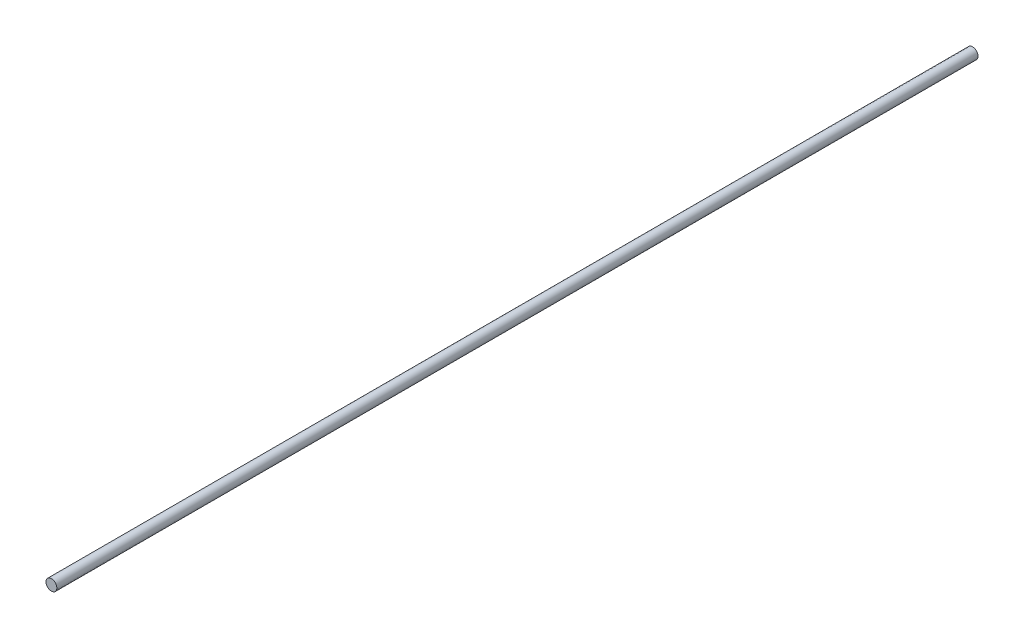
SolidWorks part; units mm, degrees
ref_plane "Front Plane" through (0, 0, 0) normal (0, 0, 1) x (1, 0, 0)
ref_plane "Top Plane" through (0, 0, 0) normal (0, 1, 0) x (1, 0, 0)
ref_plane "Right Plane" through (0, 0, 0) normal (1, 0, 0) x (0, 0, -1)
sketch "Sketch2" plane through (0, 0, 0) normal (0, 0, 1) x (1, 0, 0)
  circle A0 centre (28.0957, 18.9505) radius 20
  dimension "D1" = 40
extrude "Boss-Extrude2" add sketch "Sketch2" along normal blind 3390
sketch "Sketch4" plane through (0, 0, 0) normal (1, 0, 0) x (0, 0, -1)
  line L0 (-2617.5, 345.7459) -> (-2617.5, -278.9569) construction
  line L1 (-3390, 38.9505) -> (-3390, -1.0495) construction
  line L2 (-772.5, 345.7459) -> (-772.5, -278.9569) construction
  line L4 (0, 38.9505) -> (-3390, 38.9505) construction
  line L5 (-2647.5, 138.9505) -> (-2587.5, 138.9505)
  line L6 (-2647.5, 138.9505) -> (-2647.5, 38.9505)
  line L7 (-2647.5, 38.9505) -> (-2587.5, 38.9505)
  line L8 (-2587.5, 138.9505) -> (-2587.5, 38.9505)
  dimension "D1" = 772.5
  dimension "D2" = 1845
  dimension "D3" = 60
  dimension "D4" = 100
  dimension "D5" = 30
